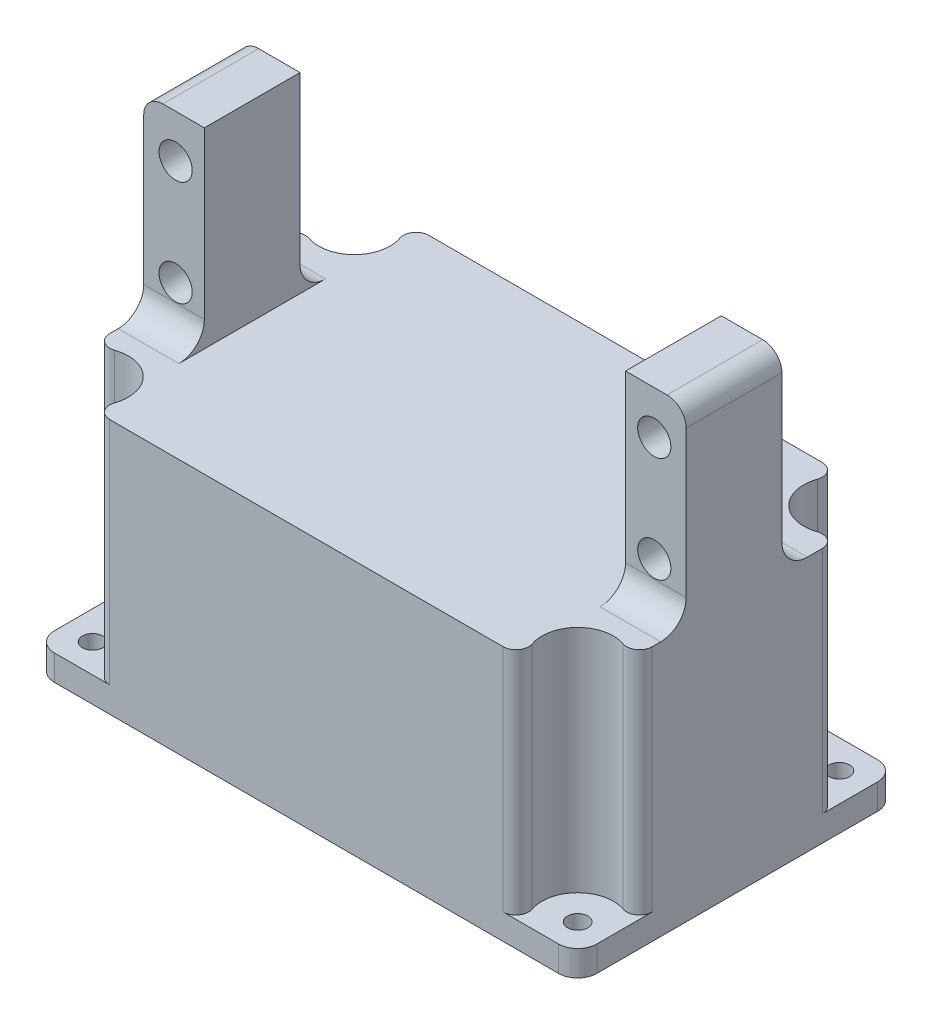
SolidWorks part; units mm, degrees
material "7050-T73510"
ref_plane "前视基准面" through (0, 0, 0) normal (0, 0, 1) x (1, 0, 0)
ref_plane "上视基准面" through (0, 0, 0) normal (0, 1, 0) x (1, 0, 0)
ref_plane "右视基准面" through (0, 0, 0) normal (1, 0, 0) x (0, 0, -1)
sketch "草图1" plane through (0, 0, 0) normal (0, 1, 0) x (1, 0, 0)
  line L1 (-39.5, -25) -> (39.5, -25)
  line L2 (-42.5, -22) -> (-42.5, 22)
  line L3 (-39.5, 25) -> (39.5, 25)
  line L4 (42.5, -22) -> (42.5, 22)
  line L5 (-42.5, -25) -> (42.5, 25) construction
  line L6 (-42.5, 25) -> (42.5, -25) construction
  arc A0 (39.5, -25) -> (42.5, -22) centre (39.5, -22) ccw
  arc A1 (-42.5, 22) -> (-39.5, 25) centre (-39.5, 22) cw
  arc A2 (-39.5, -25) -> (-42.5, -22) centre (-39.5, -22) cw
  arc A3 (39.5, 25) -> (42.5, 22) centre (39.5, 22) cw
  point P0 (0, 0)
  dimension "D3" = 3
  dimension "D1" = 85
  dimension "D2" = 50
extrude "凸台-拉伸1" add sketch "草图1" along normal blind 40
ref_plane "基准面1" through (0, 0, -7) normal (0, 0, 1) x (1, 0, 0)
sketch "草图2" plane through (0, 0, -7) normal (0, 0, 1) x (1, 0, 0)
  line L0 (-39.5, 40) -> (39.5, 40) construction
  line L1 (-42.5, 70) -> (-33, 70)
  line L2 (-42.5, 70) -> (-42.5, 40)
  line L3 (-42.5, 40) -> (-33, 40)
  line L4 (-33, 70) -> (-33, 40)
  line L5 (-42.5, 70) -> (-33, 40) construction
  line L6 (-42.5, 40) -> (-33, 70) construction
  point P0 (-37.75, 55)
  dimension "D1" = 33
  dimension "D2" = 30
  dimension "D3" = 9.5
extrude "凸台-拉伸2" add sketch "草图2" along normal blind 15
mirror "镜向1" about plane through (0, 0, 0) normal (1, 0, 0) of "凸台-拉伸2"
sketch "草图3" plane through (0, 0, 8) normal (0, 0, 1) x (1, 0, 0)
  line L0 (-39.5, 40) -> (39.5, 40) construction
  line L1 (-37.5, 46.75) -> (37.5, 46.75) construction
  line L2 (-37.5, 46.75) -> (-37.5, 63.25) construction
  line L3 (-37.5, 63.25) -> (37.5, 63.25) construction
  line L4 (37.5, 46.75) -> (37.5, 63.25) construction
  line L5 (-37.5, 46.75) -> (37.5, 63.25) construction
  line L6 (-37.5, 63.25) -> (37.5, 46.75) construction
  circle A0 centre (37.5, 63.25) radius 2.6
  circle A1 centre (37.5, 46.75) radius 2.6
  circle A2 centre (-37.5, 63.25) radius 2.6
  circle A3 centre (-37.5, 46.75) radius 2.6
  point P0 (0, 55)
  dimension "D4" = 5.2
  dimension "D1" = 15
  dimension "D2" = 16.5
  dimension "D3" = 75
extrude "切除-拉伸1" cut sketch "草图3" against normal through all
fillet "圆角1" radius 3 2 edges at (42.5, 70, 0.5) (-42.5, 70, 0.5)
fillet "圆角2" radius 4 4 edges at (-37.75, 40, -7) (37.75, 40, -7) (37.75, 40, 8) (-37.75, 40, 8)
sketch "草图4" plane through (0, 40, 0) normal (0, 1, 0) x (1, 0, 0)
  line L1 (-38, -20.5) -> (38, -20.5) construction
  line L2 (-38, -20.5) -> (-38, 20.5) construction
  line L3 (-38, 20.5) -> (38, 20.5) construction
  line L4 (38, -20.5) -> (38, 20.5) construction
  line L5 (-38, -20.5) -> (38, 20.5) construction
  line L6 (-38, 20.5) -> (38, -20.5) construction
  circle A0 centre (-38, 20.5) radius 1.6
  circle A1 centre (38, 20.5) radius 1.6
  circle A2 centre (38, -20.5) radius 1.6
  circle A3 centre (-38, -20.5) radius 1.6
  point P0 (0, 0)
  dimension "D3" = 3.2
  dimension "D1" = 76
  dimension "D2" = 41
extrude "切除-拉伸2" cut sketch "草图4" against normal through all
sketch "草图5" plane through (0, 0, 0) normal (0, -1, 0) x (1, 0, 0)
  line L25 (37.5, -20) -> (37.5, 20)
  line L26 (-37.5, -20) -> (37.5, -20)
  line L27 (-37.5, 20) -> (-37.5, -20)
  line L28 (37.5, 20) -> (-37.5, 20)
  line L29 (37.5, -20) -> (37.5, 20)
  line L30 (-37.5, -20) -> (37.5, -20)
  line L31 (-37.5, 20) -> (-37.5, -20)
  line L32 (37.5, 20) -> (-37.5, 20)
  circle A17 centre (38, 20.5) radius 8.6
  circle A18 centre (38, 20.5) radius 8.6
  circle A20 centre (-38, 20.5) radius 8.6
  circle A21 centre (-38, 20.5) radius 8.6
  circle A23 centre (-38, -20.5) radius 8.6
  circle A24 centre (-38, -20.5) radius 8.6
  circle A26 centre (38, -20.5) radius 8.6
  circle A27 centre (38, -20.5) radius 8.6
  dimension "D1" = 5
  dimension "D2" = 7
  dimension "D3" = 7
  dimension "D4" = 7
  dimension "D5" = 7
extrude "切除-拉伸3" cut sketch "草图5" against normal offset from surface (36 mm away) 4 contours A27 L29 A18 L32 A21 L31 A24 L30
fillet "圆角3" radius 2 16 edges at (31.9189, 36, -14.4189) (0, 36, -20) (-31.9189, 36, -14.4189) (-37.5, 36, 0) (-31.9189, 36, 14.4189) (0, 36, 20) (31.9189, 36, 14.4189) (37.5, 36, 0) (29.4145, 18, -20) (37.5, 18, -11.9145) (37.5, 18, 11.9145) (29.4145, 18, 20) (-37.5, 18, 11.9145) (-29.4145, 18, 20) (-29.4145, 18, -20) (-37.5, 18, -11.9145)
sketch "草图7" plane through (0, 40, 0) normal (0, 1, 0) x (1, 0, 0)
  circle A6 centre (-38, 20.5) radius 5.6
  circle A7 centre (-38, 20.5) radius 5.6
  circle A12 centre (38, 20.5) radius 5.6
  circle A13 centre (38, 20.5) radius 5.6
  circle A15 centre (-38, -20.5) radius 5.6
  circle A16 centre (-38, -20.5) radius 5.6
  circle A18 centre (38, -20.5) radius 5.6
  circle A19 centre (38, -20.5) radius 5.6
  dimension "D1" = 4
  dimension "D2" = 4
  dimension "D3" = 4
  dimension "D4" = 4
extrude "切除-拉伸4" cut sketch "草图7" against normal offset from surface (36 mm away) 4 up to face at (0, 0, 0)
fillet "圆角4" radius 2 8 edges at (34.6668, 22, 25) (42.5, 22, 17.1668) (42.5, 22, -17.1668) (34.6668, 22, -25) (-42.5, 22, -17.1668) (-34.6668, 22, -25) (-34.6668, 22, 25) (-42.5, 22, 17.1668)
